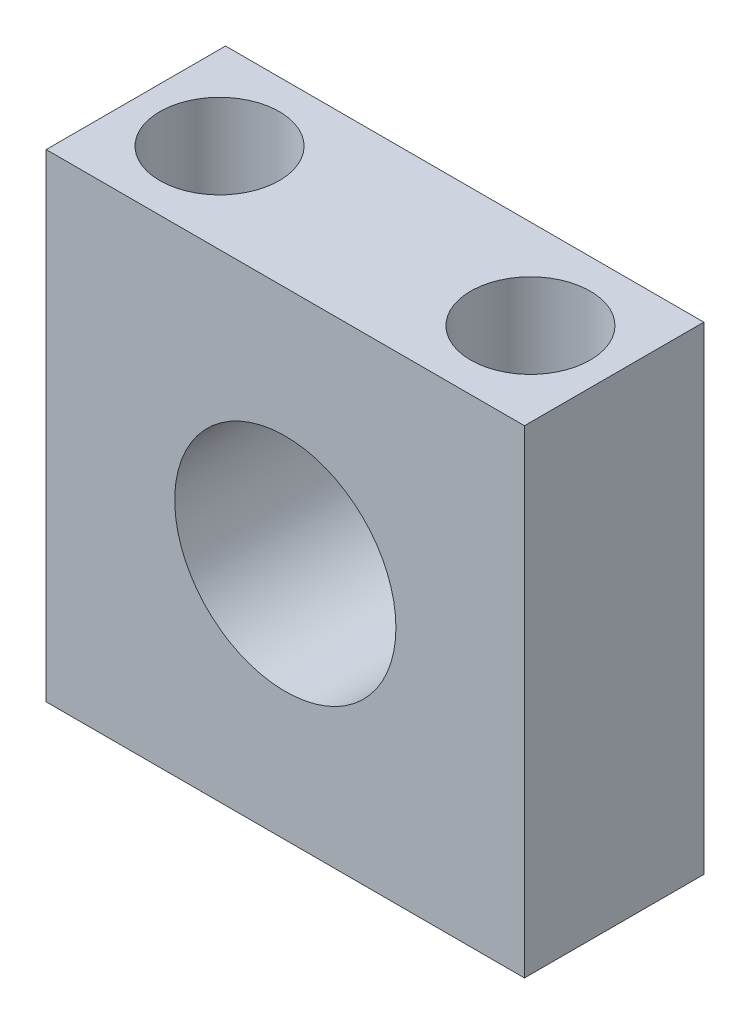
SolidWorks part; units mm, degrees
ref_plane "前视基准面" through (0, 0, 0) normal (0, 0, 1) x (1, 0, 0)
ref_plane "上视基准面" through (0, 0, 0) normal (0, 1, 0) x (1, 0, 0)
ref_plane "右视基准面" through (0, 0, 0) normal (1, 0, 0) x (0, 0, -1)
sketch "草图4" plane through (0, 0, 0) normal (0, 0, 1) x (1, 0, 0)
  line L1 (20, -20) -> (-20, -20)
  line L2 (20, -20) -> (20, 20)
  line L3 (20, 20) -> (-20, 20)
  line L4 (-20, -20) -> (-20, 20)
  line L5 (20, -20) -> (-20, 20) construction
  line L6 (20, 20) -> (-20, -20) construction
  point P0 (0, 0)
  dimension "D1" = 40
extrude "凸台-拉伸2" add sketch "草图4" along normal blind 15
hole_wizard "M20x1.5 螺纹孔2" positions "草图6" profile "草图5" tap size "M20x1.5" standard "GB"
sketch "草图6" plane through (0, 0, 15) normal (0, 0, 1) x (1, 0, 0)
  point P0 (0, 0)
sketch "草图5" plane through (0, 0, 15) normal (1, 0, 0) x (0, -1, 0)
  line L0 (0, 0) -> (0, 50.058)
  line L1 (0, 50.058) -> (9.25, 44.5)
  line L2 (9.25, 44.5) -> (9.25, 0)
  line L5 (9.25, 0) -> (0, 0)
  line L10 (0, 50.058) -> (-9.25, 44.5) construction
  line L11 (0, -6.35) -> (0, 107.95) construction
  dimension "螺纹孔钻头直径" = 18.5
  dimension "螺纹孔钻头深度" = 44.5
  dimension "导头角度" = 118
cosmetic thread "孔螺蚊线3" parameters "D1"=15, "D2"=20
hole_wizard "M6 凹头盖螺钉的柱形沉头孔1" positions "草图8" profile "草图9" counterbore size "M6" standard "Ansi Metric" end condition through all
sketch "草图8" plane through (0, 20, 0) normal (0, 1, 0) x (-1, 0, 0)
  line L0 (20, 7.5) -> (-20, 7.5) construction
  line L1 (20, 15) -> (20, 0) construction
  line L2 (-20, 15) -> (-20, 0) construction
  line L4 (0, 0) -> (0, 15) construction
  line L5 (-20, 0) -> (20, 0) construction
  line L6 (-20, 15) -> (20, 15) construction
  point P0 (13, 7.5)
  point P11 (-13, 7.5)
  dimension "D1" = 26
sketch "草图9" plane through (-13, 20, 7.5) normal (1, 0, 0) x (0, 0, 1)
  line L0 (0, 0) -> (0, 40)
  line L1 (0, 40) -> (3.3, 40)
  line L3 (3.3, 40) -> (3.3, 10)
  line L4 (3.3, 10) -> (5, 10)
  line L5 (5, 10) -> (5, 0)
  line L7 (5, 0) -> (0, 0)
  line L11 (0, -6.35) -> (0, 107.95) construction
  dimension "通孔孔直径" = 6.6
  dimension "通孔孔深度" = 40
  dimension "柱形沉头孔直径" = 10
  dimension "柱形沉头孔深度" = 10
